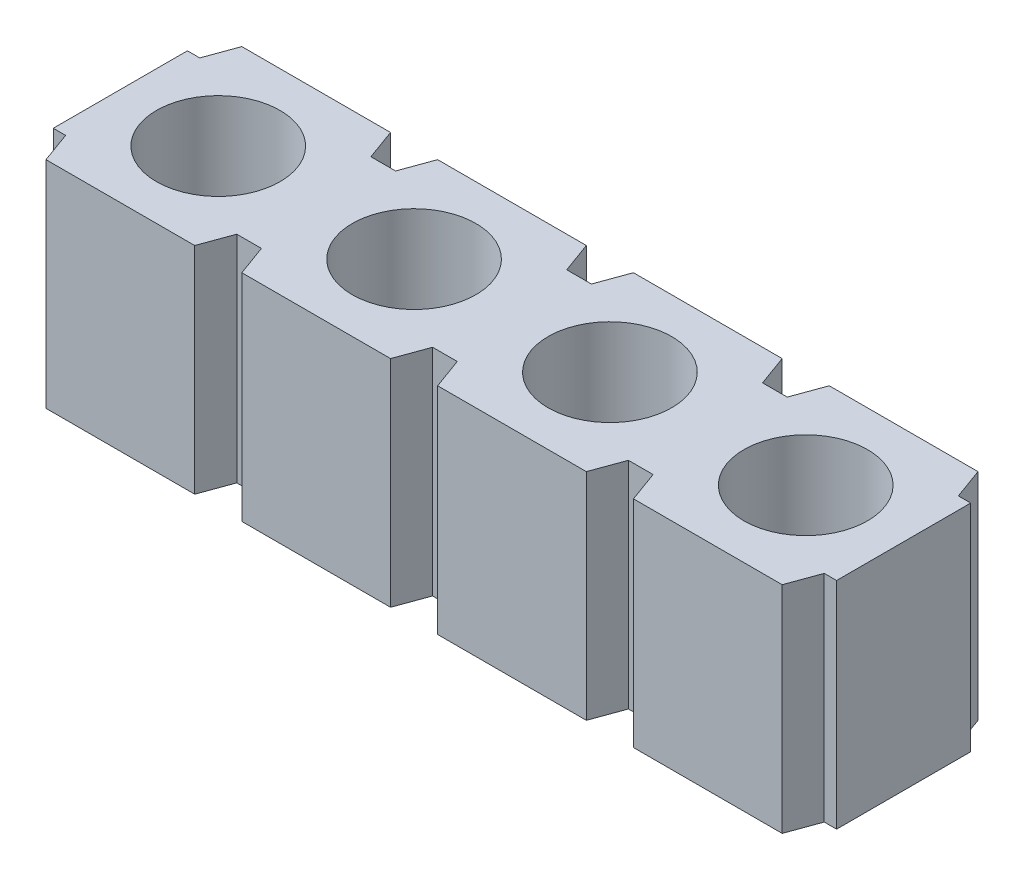
SolidWorks part; units mm, degrees
material "Nylon 46"
ref_plane "Front Plane" through (0, 0, 0) normal (0, 0, 1) x (1, 0, 0)
ref_plane "Top Plane" through (0, 0, 0) normal (0, 1, 0) x (1, 0, 0)
ref_plane "Right Plane" through (0, 0, 0) normal (1, 0, 0) x (0, 0, -1)
sketch "Sketch1" plane through (0, 0, 0) normal (0, 1, 0) x (1, 0, 0)
  line L0 (9.8544, 0.4) -> (9.6944, 0.4)
  line L1 (9.8544, 2.1399) -> (9.8544, 0.4)
  line L2 (-0.3056, 2.1399) -> (-0.1456, 2.1399)
  line L3 (-0.3056, 2.1399) -> (-0.3056, 0.4)
  line L4 (0, 0) -> (9.5487, 0)
  line L5 (0, 2.54) -> (-0.1456, 2.1399)
  line L6 (0, 0) -> (-0.1456, 0.4)
  line L7 (-0.3056, 0.4) -> (-0.1456, 0.4)
  line L9 (9.5487, 0) -> (9.6944, 0.4)
  line L10 (9.5487, 2.54) -> (9.6944, 2.1399)
  line L11 (9.8544, 2.1399) -> (9.6944, 2.1399)
  line L16 (9.5487, 2.54) -> (0, 2.54)
  dimension "D2" = 2.54
  dimension "D3" = 20
  dimension "D4" = 0.4
  dimension "D5" = 0.4
  dimension "D7" = 0.16
  dimension "INSLENGTH" = 10.16
extrude "Extrude1" add sketch "Sketch1" against normal blind 2.794
hole_wizard "Hole1" positions "3DSketch2" profile "Sketch3" legacy end condition through all
sketch3d "3DSketch2"
  line L2 (-0.3056, 0, -2.1399) -> (-0.3056, 0, -0.4) construction
  line L3 (9.5487, 0, -2.54) -> (0, 0, -2.54) construction
  point P0 (0.9644, 0, -1.27)
  dimension "D1" = 1.27
  dimension "D2" = 1.27
sketch "Sketch3" plane through (0.9644, 0, -1.27) normal (1, 0, 0) x (0, 0, 1)
  line L0 (0, 0) -> (0, 2.794)
  line L1 (0, 2.794) -> (0.8014, 2.794)
  line L2 (0.8014, 2.794) -> (0.8014, 0)
  line L3 (0.8014, 0) -> (0, 0)
  line L4 (0, 110) -> (0, -10) construction
  dimension "Diameter" = 1.6027
  dimension "Depth" = 2.794
sketch "Sketch4" plane through (0, 0, 0) normal (0, 1, 0) x (1, 0, 0)
  line L0 (1.9288, 0) -> (2.54, 0)
  line L2 (0, 0) -> (9.5487, 0) construction
  line L5 (2.0744, 0.4) -> (1.9288, 0)
  line L6 (2.3944, 0.4) -> (2.54, 0)
  line L7 (9.5487, 2.54) -> (0, 2.54) construction
  line L8 (2.0744, 0.4) -> (2.3944, 0.4)
  line L10 (2.0744, 2.1399) -> (2.3944, 2.1399)
  line L11 (2.3944, 2.1399) -> (2.54, 2.54)
  line L12 (2.0744, 2.1399) -> (1.9288, 2.54)
  line L13 (1.9288, 2.54) -> (2.54, 2.54)
  line L17 (-0.3056, 2.1399) -> (-0.3056, 0.4) construction
  dimension "D1" = 0.4
  dimension "D2" = 0.32
  dimension "D3" = 70
  dimension "D4" = 0.6112
  dimension "D5" = 0.4001
  dimension "D6" = 2.2344
extrude "Extrude2" cut sketch "Sketch4" against normal blind 2.794
pattern_linear "LPattern1" count 5 spacing 2.54 along (1, 0, 0) of "Hole1"
pattern_linear "LPattern2" count 63 spacing 2.54 along (1, 0, 0) of "Extrude2"
